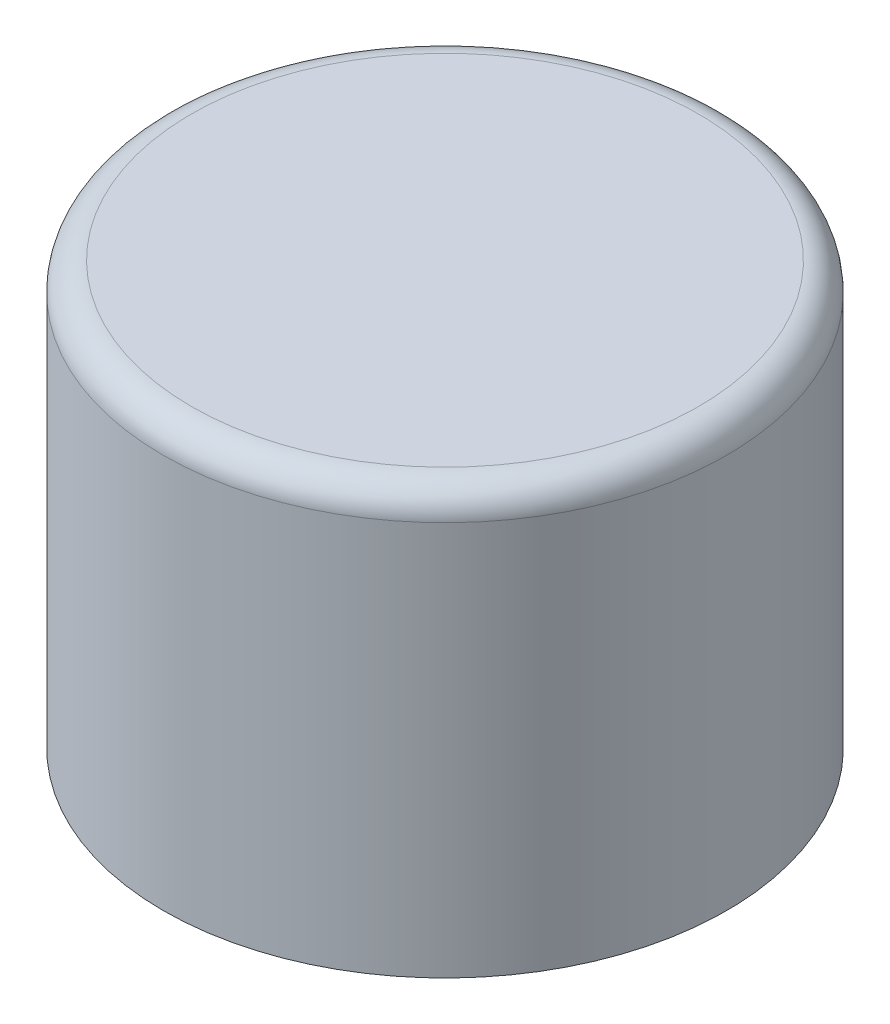
SolidWorks part; units mm, degrees
ref_plane "Plano frontal" through (0, 0, 0) normal (0, 0, 1) x (1, 0, 0)
ref_plane "Plano superior" through (0, 0, 0) normal (0, 1, 0) x (1, 0, 0)
ref_plane "Plano direito" through (0, 0, 0) normal (1, 0, 0) x (0, 0, -1)
sketch "Sketch1" plane through (0, 0, 0) normal (1, 0, 0) x (0, 0, -1)
  line L0 (0, 0) -> (0, 18.4756) construction
  line L1 (9, 0) -> (9, 12.5)
  line L2 (9, 12.5) -> (4, 12.5)
  line L3 (4, 12.5) -> (4, 8.5)
  line L4 (4, 8.5) -> (2.5, 8.5)
  line L5 (2.5, 8.5) -> (2.5, 12.5)
  line L6 (2.5, 12.5) -> (0, 12.5)
  line L7 (0, 12.5) -> (0, 15)
  line L8 (0, 15) -> (10, 15)
  line L9 (10, 15) -> (10, 0)
  line L10 (10, 0) -> (9, 0)
  point P9 (0, 15.7531)
  point P14 (0, 18.4756)
  dimension "D1" = 18
  dimension "D2" = 1
  dimension "D3" = 15
  dimension "D4" = 2.5
  dimension "D5" = 2.5
  dimension "D6" = 1.5
  dimension "D7" = 4
revolve "Revolve1" add sketch "Sketch1" angle 360 about L0
fillet "Fillet1" radius 1 1 edges at (0, 15, -10)
